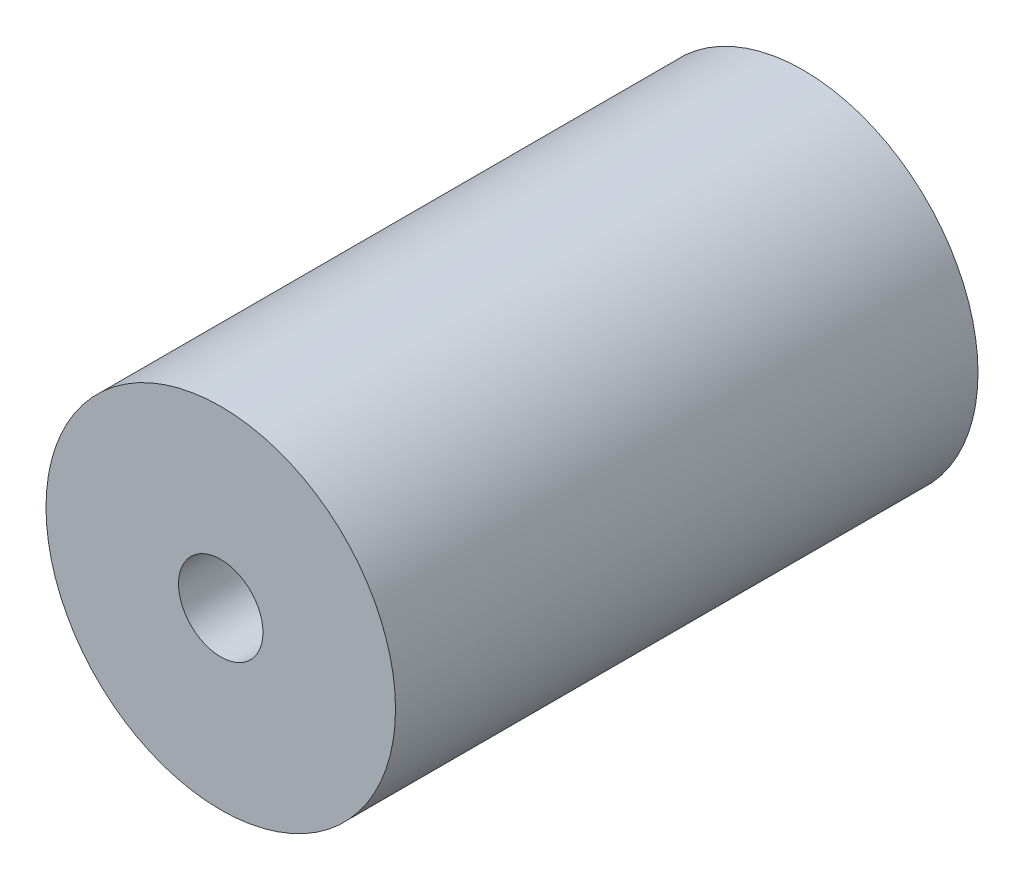
SolidWorks part; units mm, degrees
ref_plane "前视基准面" through (0, 0, 0) normal (0, 0, 1) x (1, 0, 0)
ref_plane "上视基准面" through (0, 0, 0) normal (0, 1, 0) x (1, 0, 0)
ref_plane "右视基准面" through (0, 0, 0) normal (1, 0, 0) x (0, 0, -1)
sketch "草图1" plane through (0, 0, 0) normal (0, 0, 1) x (1, 0, 0)
  circle A0 centre (0, 0) radius 6
  circle A1 centre (0, 0) radius 1.45
  dimension "D1" = 12
  dimension "D2" = 2.9
extrude "凸台-拉伸1" add sketch "草图1" along normal blind 20
